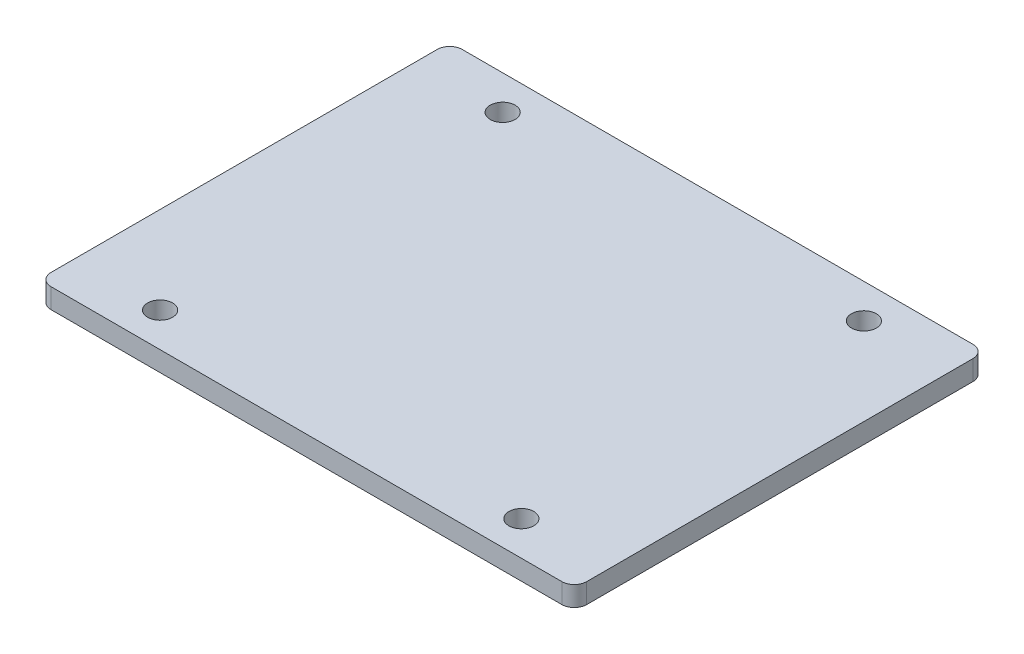
SolidWorks part; units mm, degrees
ref_plane "Plan de face" through (0, 0, 0) normal (0, 0, 1) x (1, 0, 0)
ref_plane "Plan de dessus" through (0, 0, 0) normal (0, 1, 0) x (1, 0, 0)
ref_plane "Plan de droite" through (0, 0, 0) normal (1, 0, 0) x (0, 0, -1)
sketch "Esquisse1" plane through (0, 0, 0) normal (0, 1, 0) x (1, 0, 0)
  line L1 (-20.5, -16.5) -> (20.5, -16.5)
  line L2 (-21.5, -15.5) -> (-21.5, 15.5)
  line L3 (-20.5, 16.5) -> (20.5, 16.5)
  line L4 (21.5, -15.5) -> (21.5, 15.5)
  line L5 (-21.5, -16.5) -> (21.5, 16.5) construction
  line L6 (-21.5, 16.5) -> (21.5, -16.5) construction
  arc A0 (-20.5, -16.5) -> (-21.5, -15.5) centre (-20.5, -15.5) cw
  arc A1 (20.5, -16.5) -> (21.5, -15.5) centre (20.5, -15.5) ccw
  arc A2 (20.5, 16.5) -> (21.5, 15.5) centre (20.5, 15.5) cw
  arc A3 (-21.5, 15.5) -> (-20.5, 16.5) centre (-20.5, 15.5) cw
  point P0 (0, 0)
  dimension "D3" = 1
  dimension "D1" = 43
  dimension "D2" = 33
extrude "Boss.-Extru.1" add sketch "Esquisse1" along normal blind 1.6
sketch "Esquisse2" plane through (0, 1.6, 0) normal (0, 1, 0) x (1, 0, 0)
  circle A0 centre (-14.5, 13.75) radius 1
  circle A1 centre (14.5, 13.75) radius 1
  circle A2 centre (14.5, -13.75) radius 1
  circle A3 centre (-14.5, -13.75) radius 1
extrude "Enlèv. mat.-Extru.1" cut sketch "Esquisse2" against normal up to next
